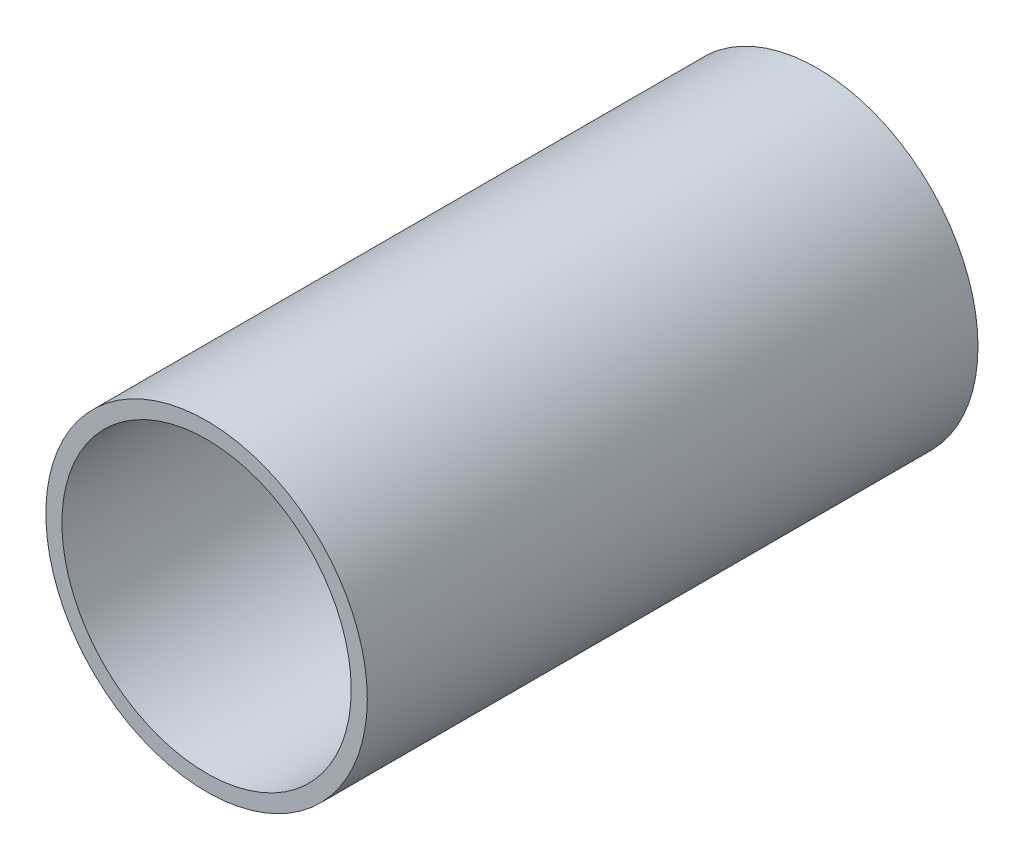
SolidWorks part; units mm, degrees
ref_plane "前视基准面" through (0, 0, 0) normal (0, 0, 1) x (1, 0, 0)
ref_plane "上视基准面" through (0, 0, 0) normal (0, 1, 0) x (1, 0, 0)
ref_plane "右视基准面" through (0, 0, 0) normal (1, 0, 0) x (0, 0, -1)
sketch "草图1" plane through (0, 0, 0) normal (0, 0, 1) x (1, 0, 0)
  circle A0 centre (-1.5694, 0) radius 10
  circle A1 centre (-1.5694, 0) radius 9
extrude "凸台-拉伸1" add sketch "草图1" along normal blind 38
